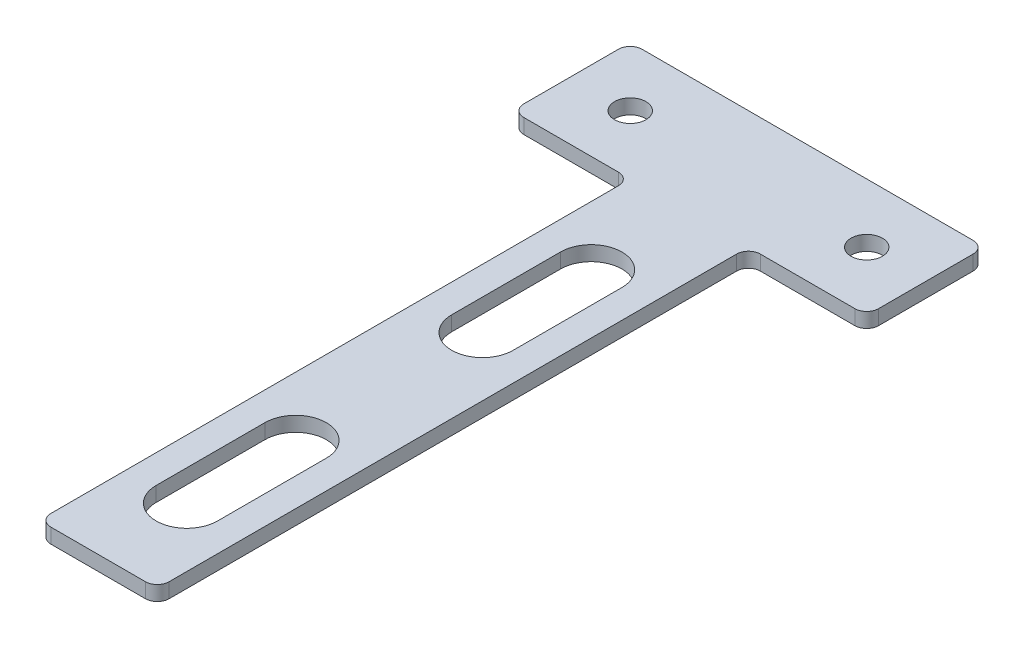
SolidWorks part; units mm, degrees
material "5052-O"
ref_plane "Front Plane" through (0, 0, 0) normal (0, 0, 1) x (1, 0, 0)
ref_plane "Top Plane" through (0, 0, 0) normal (0, 1, 0) x (1, 0, 0)
ref_plane "Right Plane" through (0, 0, 0) normal (1, 0, 0) x (0, 0, -1)
sketch "Sketch1" plane through (0, 0, 0) normal (0, 1, 0) x (1, 0, 0)
  line L0 (-12.7, 50.8) -> (-12.7, -76.2)
  line L1 (-12.7, -76.2) -> (12.7, -76.2)
  line L2 (-12.7, 50.8) -> (-12.7, 76.2) construction
  line L3 (-12.7, 76.2) -> (12.7, 76.2)
  line L4 (12.7, 50.8) -> (12.7, 76.2) construction
  line L5 (-12.7, -76.2) -> (12.7, 76.2) construction
  line L6 (-12.7, 76.2) -> (12.7, -76.2) construction
  line L7 (-12.7, 76.2) -> (-38.1, 76.2)
  line L8 (-12.7, 76.2) -> (-12.7, 50.8)
  line L9 (-12.7, 50.8) -> (-38.1, 50.8)
  line L10 (-38.1, 76.2) -> (-38.1, 50.8)
  line L11 (12.7, 76.2) -> (38.1, 76.2)
  line L12 (12.7, 76.2) -> (12.7, 50.8)
  line L13 (12.7, 50.8) -> (38.1, 50.8)
  line L14 (38.1, 76.2) -> (38.1, 50.8)
  line L15 (12.7, -76.2) -> (12.7, 50.8)
  point P0 (0, 0)
  dimension "D1" = 25.4
  dimension "D2" = 152.4
  dimension "D3" = 25.4
  dimension "D4" = 25.4
extrude "Boss-Extrude1" add sketch "Sketch1" along normal blind 3.175 contours L7 L10 L9 L8 | L1 L15 L12 L3 L8 L0 | L14 L11 L12 L13
sketch "Sketch2" plane through (0, 3.175, 0) normal (0, 1, 0) x (1, 0, 0)
  line L0 (0, 76.2) -> (0, -76.2) construction
  line L1 (38.1, 76.2) -> (-38.1, 76.2) construction
  line L2 (-12.7, -76.2) -> (12.7, -76.2) construction
  line L3 (-38.1, 63.5) -> (38.1, 63.5) construction
  line L4 (-38.1, 76.2) -> (-38.1, 50.8) construction
  line L5 (38.1, 76.2) -> (38.1, 50.8) construction
  line L6 (0, 29.718) -> (0, 6.35) construction
  line L7 (6.604, 29.718) -> (6.604, 6.35)
  line L8 (-6.604, 29.718) -> (-6.604, 6.35)
  line L9 (0, -33.782) -> (0, -57.15) construction
  line L10 (6.604, -33.782) -> (6.604, -57.15)
  line L11 (-6.604, -33.782) -> (-6.604, -57.15)
  circle A0 centre (-25.4, 63.5) radius 3.3734
  circle A1 centre (25.4, 63.5) radius 3.3734
  arc A2 (6.604, 29.718) -> (-6.604, 29.718) centre (0, 29.718) ccw
  arc A3 (-6.604, 6.35) -> (6.604, 6.35) centre (0, 6.35) ccw
  arc A4 (6.604, -33.782) -> (-6.604, -33.782) centre (0, -33.782) ccw
  arc A5 (-6.604, -57.15) -> (6.604, -57.15) centre (0, -57.15) ccw
  point P18 (0, 18.034)
  point P23 (0, -45.466)
  dimension "D1" = 23.368
  dimension "D2" = 12.7
  dimension "D3" = 6.7469
  dimension "D4" = 12.7
  dimension "D6" = 6.604
  dimension "D9" = 6.604
  dimension "D5" = 19.05
  dimension "D7" = 23.368
  dimension "D8" = 69.85
extrude "Cut-Extrude1" cut sketch "Sketch2" against normal blind 3.175
fillet "Fillet1" radius 2.54 8 edges at (-12.7, 1.5875, 76.2) (12.7, 1.5875, 76.2) (12.7, 1.5875, -50.8) (-12.7, 1.5875, -50.8) (-38.1, 1.5875, -50.8) (38.1, 1.5875, -50.8) (38.1, 1.5875, -76.2) (-38.1, 1.5875, -76.2)
